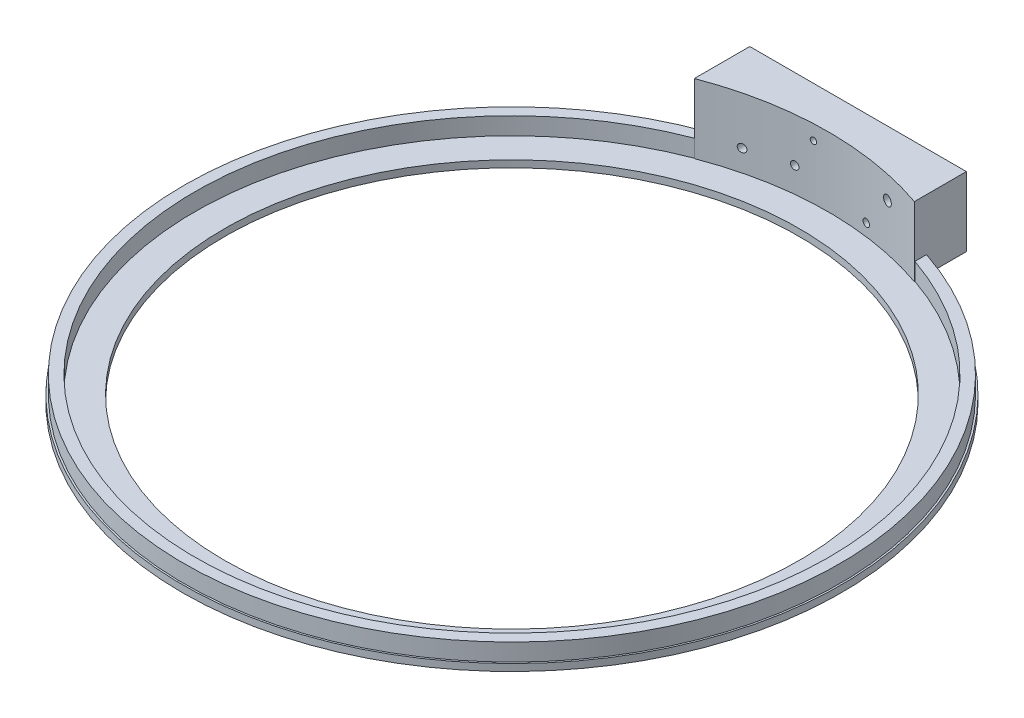
SolidWorks part; units mm, degrees
ref_plane "Front Plane" through (0, 0, 0) normal (0, 0, 1) x (1, 0, 0)
ref_plane "Top Plane" through (0, 0, 0) normal (0, 1, 0) x (1, 0, 0)
ref_plane "Right Plane" through (0, 0, 0) normal (1, 0, 0) x (0, 0, -1)
sketch "Sketch1" plane through (0, 0, 0) normal (0, 1, 0) x (1, 0, 0)
  circle A0 centre (0, 0) radius 95
  circle A1 centre (0, 0) radius 82.849
extrude "Boss-Extrude1" add sketch "Sketch1" along normal blind 2
sketch "Sketch3" plane through (0, 2, 0) normal (0, 1, 0) x (1, 0, 0)
  circle A0 centre (0, 0) radius 94.4944
  circle A1 centre (0, 0) radius 91.3331
extrude "Boss-Extrude2" add sketch "Sketch3" along normal blind 5
sketch "Sketch4" plane through (0, 2, 0) normal (0, 1, 0) x (1, 0, 0)
  line L1 (-32.5892, 84.1457) -> (29.8508, 84.1457)
  line L2 (-32.5892, 84.1457) -> (-32.5892, 101.1451)
  line L3 (-32.5892, 101.1451) -> (29.8508, 101.1451)
  line L4 (29.8508, 84.1457) -> (29.8508, 101.1451)
extrude "Boss-Extrude3" add sketch "Sketch4" along normal blind 20
sketch "Sketch5" plane through (0, 2, 0) normal (0, 1, 0) x (1, 0, 0)
  circle A0 centre (0, 0) radius 91.1877
extrude "Cut-Extrude1" cut sketch "Sketch5" along normal up to surface (20 mm away) up to face at (-1.3692, 22, -92.6454)
sketch "Sketch6" plane through (0, 0, -101.1451) normal (0, 0, -1) x (-1, 0, 0)
  circle A0 centre (22.1124, 8.2038) radius 1.1333
  circle A1 centre (4.1799, 17.7241) radius 0.8841
  circle A2 centre (-11.7232, 5.5135) radius 1.0638
  circle A3 centre (9.1923, 9.2206) radius 1.1168
  circle A4 centre (-19.0901, 15.3734) radius 1.4226
extrude "Cut-Extrude2" cut sketch "Sketch6" against normal blind 25
